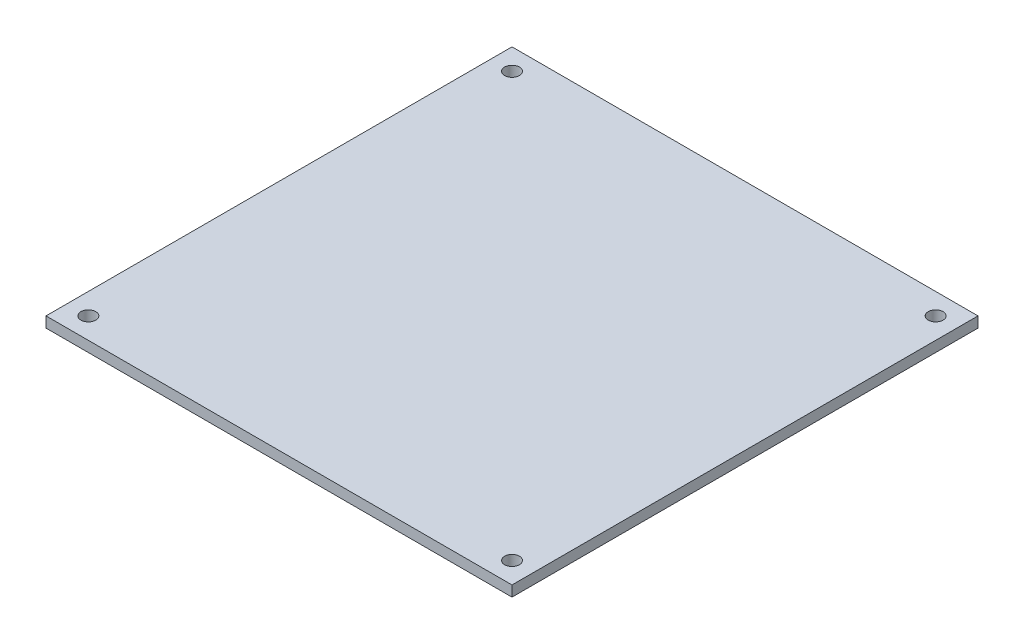
SolidWorks part; units mm, degrees
ref_plane "Front Plane" through (0, 0, 0) normal (0, 0, 1) x (1, 0, 0)
ref_plane "Top Plane" through (0, 0, 0) normal (0, 1, 0) x (1, 0, 0)
ref_plane "Right Plane" through (0, 0, 0) normal (1, 0, 0) x (0, 0, -1)
sketch "Sketch1" plane through (0, 0, 0) normal (0, 1, 0) x (1, 0, 0)
  line L1 (-110, -110) -> (110, -110)
  line L2 (-110, -110) -> (-110, 110)
  line L3 (-110, 110) -> (110, 110)
  line L4 (110, -110) -> (110, 110)
  line L5 (-110, -110) -> (110, 110) construction
  line L6 (-110, 110) -> (110, -110) construction
  point P0 (0, 0)
  dimension "D1" = 220
  dimension "D2" = 220
extrude "Boss-Extrude1" add sketch "Sketch1" along normal mid plane 5
sketch "Sketch4" plane through (0, 2.5, 0) normal (0, 1, 0) x (1, 0, 0)
  line L0 (-110, 110) -> (-110, -110) construction
  line L1 (110, 110) -> (-110, 110) construction
  circle A0 centre (-100, 100) radius 3.5
  dimension "D1" = 7
  dimension "D2" = 10
  dimension "D3" = 10
extrude "Cut-Extrude1" cut sketch "Sketch4" against normal blind 5
mirror "Mirror3" about plane through (0, 0, 0) normal (1, 0, 0) of "Cut-Extrude1"
mirror "Mirror4" about plane through (0, 0, 0) normal (0, 0, 1) of "Mirror3", "Cut-Extrude1"
